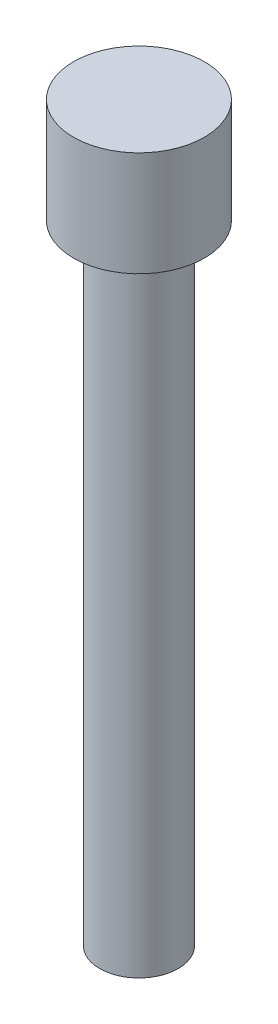
SolidWorks part; units mm, degrees
ref_plane "Piano frontale" through (0, 0, 0) normal (0, 0, 1) x (1, 0, 0)
ref_plane "Piano superiore" through (0, 0, 0) normal (0, 1, 0) x (1, 0, 0)
ref_plane "Piano destro" through (0, 0, 0) normal (1, 0, 0) x (0, 0, -1)
sketch "Schizzo1" plane through (0, 0, 0) normal (0, 1, 0) x (1, 0, 0)
  circle A0 centre (0, 0) radius 1.5
  dimension "D1" = 3
extrude "Estrusione-Estrusione1" add sketch "Schizzo1" along normal blind 24
sketch "Schizzo2" plane through (0, 24, 0) normal (0, 1, 0) x (1, 0, 0)
  circle A0 centre (0, 0) radius 2.5
  dimension "D1" = 5
extrude "Estrusione-Estrusione2" add sketch "Schizzo2" along normal blind 4
